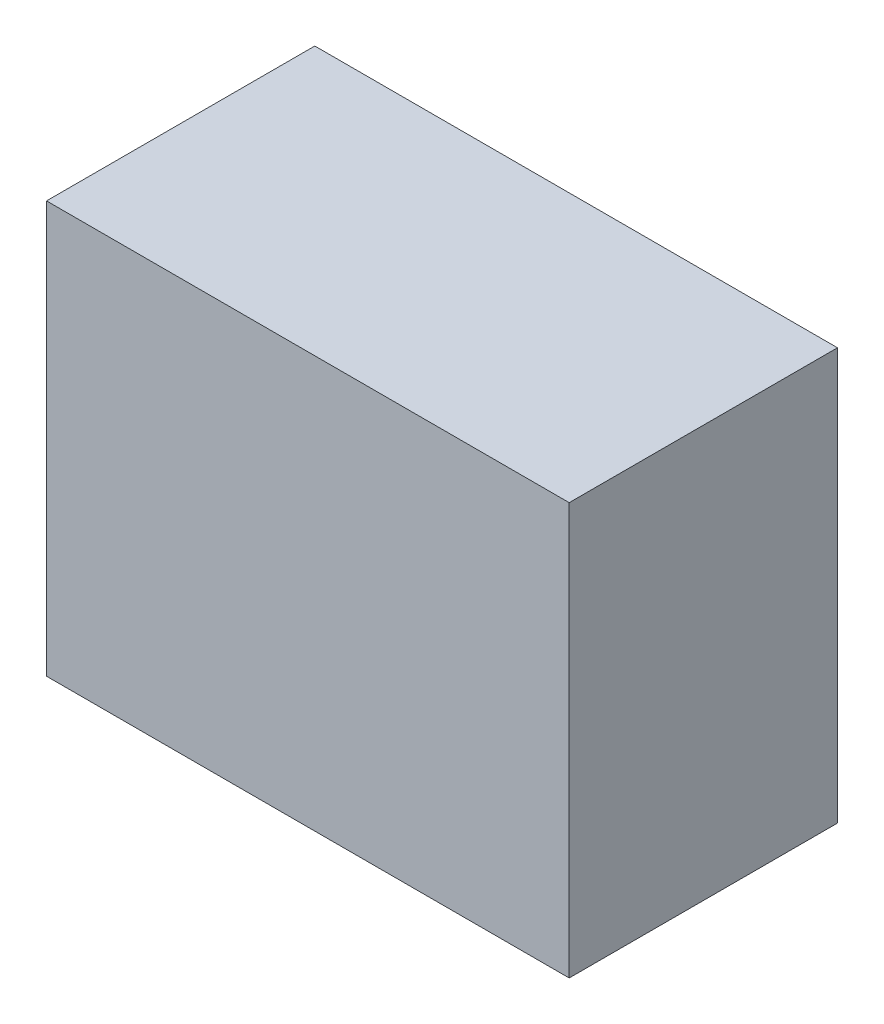
SolidWorks part; units mm, degrees
ref_plane "Front Plane" through (0, 0, 0) normal (0, 0, 1) x (1, 0, 0)
ref_plane "Top Plane" through (0, 0, 0) normal (0, 1, 0) x (1, 0, 0)
ref_plane "Right Plane" through (0, 0, 0) normal (1, 0, 0) x (0, 0, -1)
sketch "Sketch1" plane through (0, 0, 0) normal (0, 1, 0) x (1, 0, 0)
  line L1 (-56.5, -29) -> (56.5, -29)
  line L2 (-56.5, -29) -> (-56.5, 29)
  line L3 (-56.5, 29) -> (56.5, 29)
  line L4 (56.5, -29) -> (56.5, 29)
  line L5 (-56.5, -29) -> (56.5, 29) construction
  line L6 (-56.5, 29) -> (56.5, -29) construction
  point P0 (0, 0)
  dimension "D1" = 58
  dimension "D2" = 113
extrude "Boss-Extrude1" add sketch "Sketch1" along normal blind 89 contours L3 L4 L1 L2
